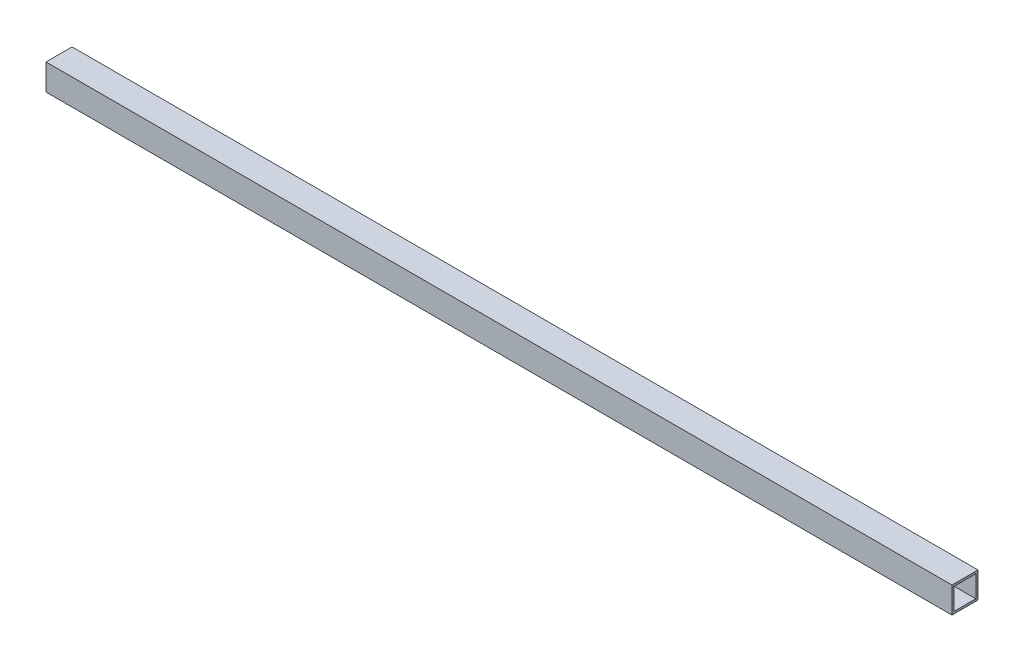
SolidWorks part; units mm, degrees
ref_plane "Front Plane" through (0, 0, 0) normal (0, 0, 1) x (1, 0, 0)
ref_plane "Top Plane" through (0, 0, 0) normal (0, 1, 0) x (1, 0, 0)
ref_plane "Right Plane" through (0, 0, 0) normal (1, 0, 0) x (0, 0, -1)
sketch "Sketch1" plane through (-989.4937, 0, 0) normal (1, 0, 0) x (0, 0, -1)
  line L0 (-768.0453, 79.306) -> (-768.0453, 63.431)
  line L1 (-769.6328, 80.8935) -> (-750.5828, 80.8935)
  line L2 (-769.6328, 80.8935) -> (-769.6328, 61.8435)
  line L3 (-769.6328, 61.8435) -> (-750.5828, 61.8435)
  line L4 (-750.5828, 80.8935) -> (-750.5828, 61.8435)
  line L5 (-768.0453, 63.431) -> (-752.1703, 63.431)
  line L6 (-752.1703, 79.306) -> (-752.1703, 63.431)
  line L7 (-768.0453, 79.306) -> (-752.1703, 79.306)
  line L8 (-363.6828, 80.8935) -> (-825.5828, 80.8935) construction
  line L9 (-594.6328, 87.8785) -> (-594.6328, 73.9085) construction
  dimension "D1" = 1.5875
  dimension "D2" = 19.05
  dimension "D3" = 175
extrude "Boss-Extrude1" add sketch "Sketch1" along normal up to surface (661.9 mm away)
